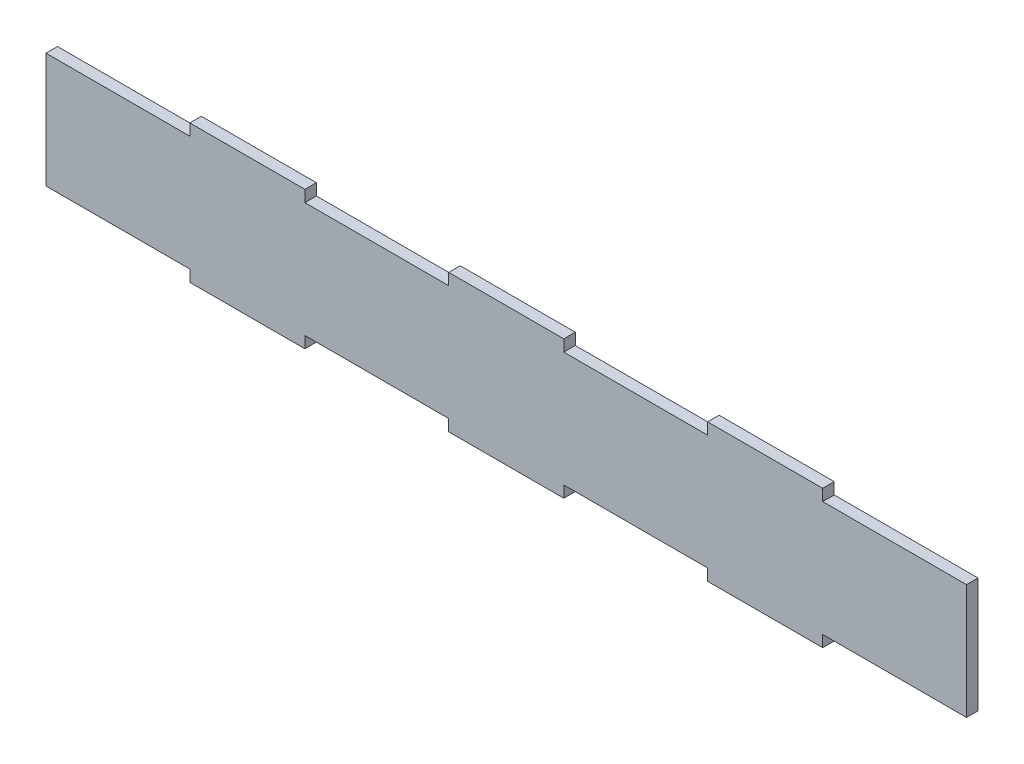
SolidWorks part; units mm, degrees
ref_plane "Спереди" through (0, 0, 0) normal (0, 0, 1) x (1, 0, 0)
ref_plane "Сверху" through (0, 0, 0) normal (0, 1, 0) x (1, 0, 0)
ref_plane "Справа" through (0, 0, 0) normal (1, 0, 0) x (0, 0, -1)
sketch "Эскиз1" plane through (0, 0, 0) normal (0, 0, 1) x (1, 0, 0)
  line L1 (0, 0) -> (160, 0)
  line L2 (0, 0) -> (0, 24)
  line L3 (0, 24) -> (160, 24)
  line L4 (160, 0) -> (160, 24)
  line L5 (0, 24) -> (25, 24)
  line L6 (0, 24) -> (0, 22)
  line L7 (0, 22) -> (25, 22)
  line L8 (25, 24) -> (25, 22)
  line L9 (45, 24) -> (70, 24)
  line L10 (45, 24) -> (45, 22)
  line L11 (45, 22) -> (70, 22)
  line L12 (70, 24) -> (70, 22)
  line L13 (90, 24) -> (115, 24)
  line L14 (90, 24) -> (90, 22)
  line L15 (90, 22) -> (115, 22)
  line L16 (115, 24) -> (115, 22)
  line L17 (0, 0) -> (25, 0)
  line L18 (0, 0) -> (0, 2)
  line L19 (0, 2) -> (25, 2)
  line L20 (25, 0) -> (25, 2)
  line L21 (45, 0) -> (70, 0)
  line L22 (45, 0) -> (45, 2)
  line L23 (45, 2) -> (70, 2)
  line L24 (70, 0) -> (70, 2)
  line L25 (90, 0) -> (115, 0)
  line L26 (90, 0) -> (90, 2)
  line L27 (90, 2) -> (115, 2)
  line L28 (115, 0) -> (115, 2)
  line L29 (160, 24) -> (135, 24)
  line L30 (160, 24) -> (160, 22)
  line L31 (160, 22) -> (135, 22)
  line L32 (135, 24) -> (135, 22)
  line L33 (160, 0) -> (135, 0)
  line L34 (160, 0) -> (160, 2)
  line L35 (160, 2) -> (135, 2)
  line L36 (135, 0) -> (135, 2)
  dimension "D1" = 24
  dimension "D2" = 160
  dimension "D3" = 2
  dimension "D4" = 2
  dimension "D5" = 2
  dimension "D6" = 2
  dimension "D7" = 2
  dimension "D8" = 2
  dimension "D9" = 25
  dimension "D10" = 25
  dimension "D11" = 25
  dimension "D12" = 25
  dimension "D13" = 25
  dimension "D14" = 25
  dimension "D15" = 20
  dimension "D16" = 20
  dimension "D17" = 20
  dimension "D18" = 20
  dimension "D19" = 20
  dimension "D20" = 20
  dimension "D21" = 2
  dimension "D22" = 2
extrude "Бобышка-Вытянуть1" add sketch "Эскиз1" along normal blind 2 contours L1 L36 L35 L4 L31 L32 L3 L16 L15 L14 L12 L11 L10 L8 L7 L2 L19 L20 L22 L23 L24 L26 L27 L28
